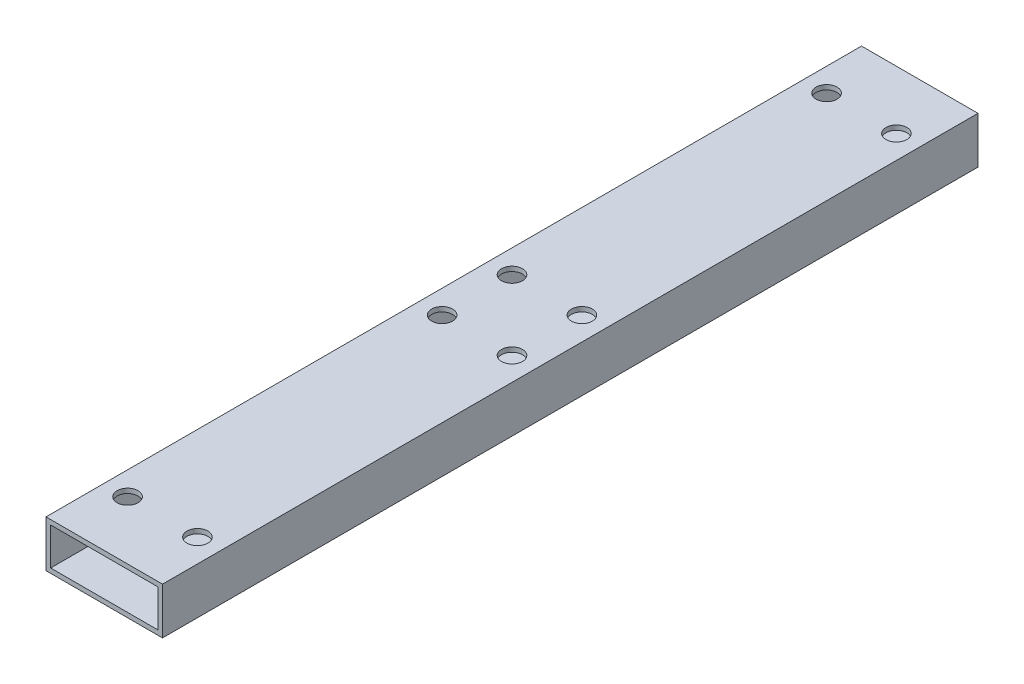
SolidWorks part; units mm, degrees
ref_plane "Спереди" through (0, 0, 0) normal (0, 0, 1) x (1, 0, 0)
ref_plane "Сверху" through (0, 0, 0) normal (0, 1, 0) x (1, 0, 0)
ref_plane "Справа" through (0, 0, 0) normal (1, 0, 0) x (0, 0, -1)
sketch "Эскиз1" plane through (0, 0, 0) normal (0, 0, 1) x (1, 0, 0)
  line L1 (-25, -10) -> (25, -10)
  line L2 (-25, -10) -> (-25, 10)
  line L3 (-25, 10) -> (25, 10)
  line L4 (25, -10) -> (25, 10)
  line L5 (-25, -10) -> (25, 10) construction
  line L6 (-25, 10) -> (25, -10) construction
  point P0 (0, 0)
  dimension "D1" = 20
  dimension "D2" = 50
extrude "Бобышка-Вытянуть1" add sketch "Эскиз1" along normal blind 350
sketch "Эскиз2" plane through (0, 0, 350) normal (0, 0, 1) x (1, 0, 0)
  line L0 (25, 10) -> (-25, 10) construction
  line L1 (-23, -8) -> (23, -8)
  line L2 (-23, -8) -> (-23, 8)
  line L3 (-23, 8) -> (23, 8)
  line L4 (23, -8) -> (23, 8)
  line L5 (-23, -8) -> (23, 8) construction
  line L6 (-23, 8) -> (23, -8) construction
  line L7 (-25, 10) -> (-25, -10) construction
  point P0 (0, 0)
  dimension "D1" = 2
  dimension "D2" = 2
extrude "Вырез-Вытянуть1" cut sketch "Эскиз2" against normal through all
sketch "Эскиз3" plane through (0, 10, 0) normal (0, 1, 0) x (-1, 0, 0)
  line L0 (-25, 350) -> (25, 300) construction
  line L1 (-25, 0) -> (25, 0) construction
  line L2 (-25, 0) -> (-25, 350) construction
  line L3 (-25, 350) -> (25, 350) construction
  line L4 (25, 0) -> (25, 350) construction
  line L5 (25, 300) -> (-25, 300) construction
  line L6 (-15, 300) -> (-15, 325) construction
  line L7 (-15, 325) -> (-15, 350) construction
  line L8 (15, 325) -> (15, 350) construction
  line L9 (15, 325) -> (15, 300) construction
  line L10 (15, 325) -> (25, 325) construction
  line L11 (-15, 325) -> (-25, 325) construction
  line L12 (-25, 0) -> (25, 50) construction
  line L13 (-15, 25) -> (-15, 0) construction
  line L14 (-15, 0) -> (-15, 25) construction
  line L15 (-15, 25) -> (-15, 50) construction
  line L16 (-25, 50) -> (25, 50) construction
  line L17 (15, 25) -> (15, 0) construction
  line L18 (15, 25) -> (15, 50) construction
  line L19 (-15, 25) -> (-25, 25) construction
  line L20 (15, 25) -> (25, 25) construction
  line L21 (-25, 350) -> (25, 0) construction
  line L23 (25, 200) -> (-25, 200) construction
  line L24 (25, 200) -> (25, 150) construction
  line L25 (25, 150) -> (-25, 150) construction
  line L26 (-25, 200) -> (-25, 150) construction
  line L27 (25, 200) -> (-25, 150) construction
  line L28 (25, 150) -> (-25, 200) construction
  circle A0 centre (-15, 325) radius 4.5
  circle A1 centre (15, 325) radius 4.5
  circle A2 centre (-15, 25) radius 4.5
  circle A3 centre (15, 25) radius 4.5
  circle A4 centre (-15, 160) radius 4.5
  circle A5 centre (-15, 190) radius 4.5
  circle A6 centre (15, 190) radius 4.5
  circle A7 centre (15, 160) radius 4.5
  point P26 (0, 175)
  dimension "D2" = 10
  dimension "D4" = 9
  dimension "D1" = 50
  dimension "D3" = 10
  dimension "D5" = 50
  dimension "D6" = 10
  dimension "D7" = 10
  dimension "D8" = 50
extrude "Вырез-Вытянуть3" cut sketch "Эскиз3" against normal through all
